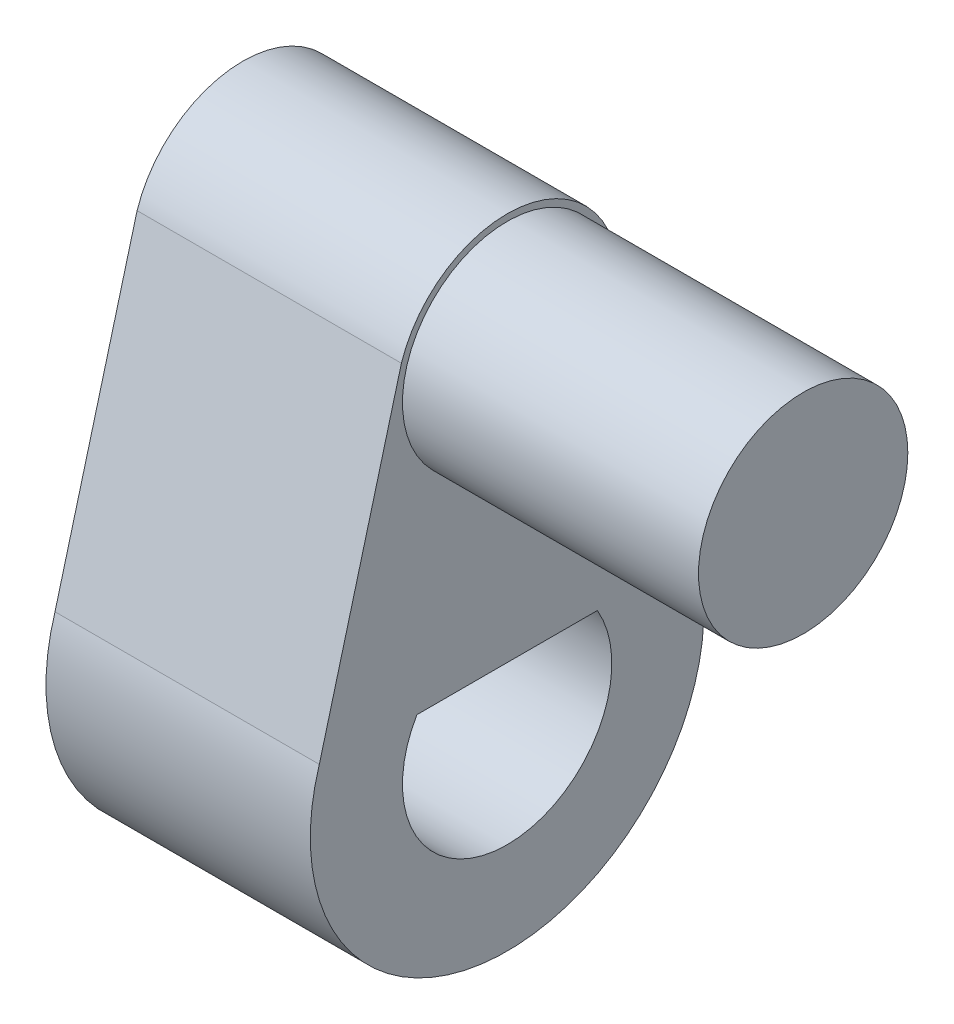
SolidWorks part; units mm, degrees
ref_plane "Front Plane" through (0, 0, 0) normal (0, 0, 1) x (1, 0, 0)
ref_plane "Top Plane" through (0, 0, 0) normal (0, 1, 0) x (1, 0, 0)
ref_plane "Right Plane" through (0, 0, 0) normal (1, 0, 0) x (0, 0, -1)
sketch "Sketch3" plane through (0, 0, 0) normal (1, 0, 0) x (0, 0, -1)
  line L2 (-54.6708, 30.9688) -> (-55.4472, 28.071)
  line L3 (-52.6708, 30.9688) -> (-51.8943, 28.071)
  arc A0 (-52.6708, 30.9688) -> (-54.6708, 30.9688) centre (-53.6708, 30.6404) ccw
  arc A1 (-55.4472, 28.071) -> (-51.8943, 28.071) centre (-53.6708, 27.5142) ccw
  dimension "D3" = 3
  dimension "D4" = 3
  dimension "D5" = 0
extrude "Boss-Extrude2" add sketch "Sketch3" along normal blind 2.5
sketch "Sketch4" plane through (2.5, 0, 0) normal (1, 0, 0) x (0, 0, -1)
  circle A0 centre (-53.6708, 27.5142) radius 0.99
  dimension "D1" = 1.98
extrude "Cut-Extrude2" cut sketch "Sketch4" against normal through all
sketch "Sketch6" plane through (2.5, 0, 0) normal (1, 0, 0) x (0, 0, -1)
  circle A0 centre (-53.6708, 30.6404) radius 0.99
  dimension "D1" = 1.98
extrude "Boss-Extrude4" add sketch "Sketch6" along normal blind 2.8
sketch "Sketch7" plane through (2.5, 0, 0) normal (1, 0, 0) x (0, 0, -1)
  line L1 (-54.6674, 28.0164) -> (-52.6476, 28.0164)
  line L2 (-54.6674, 28.0164) -> (-54.6674, 28.8013)
  line L3 (-54.6674, 28.8013) -> (-52.6476, 28.8013)
  line L4 (-52.6476, 28.0164) -> (-52.6476, 28.8013)
extrude "Boss-Extrude5" add sketch "Sketch7" against normal up to surface (2.5 mm away) up to face at (0, 27.5142, 52.6808)
fillet "Fillet1" radius 0.2 2 edges at (0, 26.5242, 53.6708) (0, 28.0164, 53.6708)
